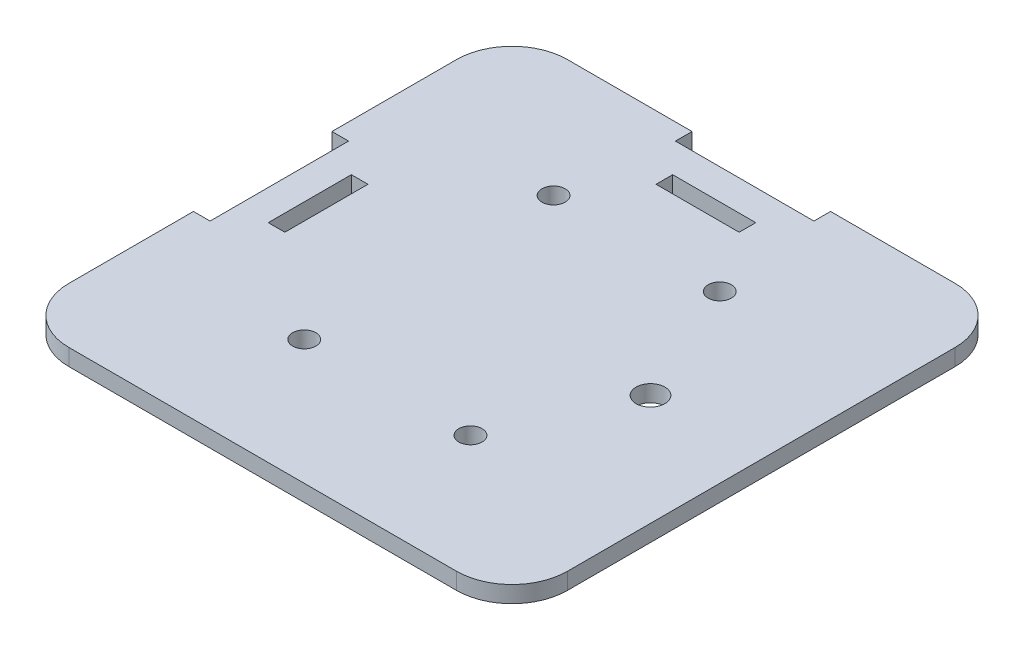
SolidWorks part; units mm, degrees
ref_plane "Front Plane" through (0, 0, 0) normal (0, 0, 1) x (1, 0, 0)
ref_plane "Top Plane" through (0, 0, 0) normal (0, 1, 0) x (1, 0, 0)
ref_plane "Right Plane" through (0, 0, 0) normal (1, 0, 0) x (0, 0, -1)
sketch "Sketch1" plane through (0, 0, 0) normal (0, 1, 0) x (1, 0, 0)
  line L1 (35, -45) -> (-35, -45)
  line L2 (45, -35) -> (45, 35)
  line L3 (35, 45) -> (-35, 45)
  line L4 (-45, -35) -> (-45, 35)
  line L5 (45, -45) -> (-45, 45) construction
  line L6 (45, 45) -> (-45, -45) construction
  line L7 (-45, 12.5) -> (-42, 12.5)
  line L8 (-45, 12.5) -> (-45, -12.5)
  line L9 (-45, -12.5) -> (-42, -12.5)
  line L10 (-42, 12.5) -> (-42, -12.5)
  line L11 (-12.5, 45) -> (12.5, 45)
  line L12 (-12.5, 45) -> (-12.5, 42)
  line L13 (-12.5, 42) -> (12.5, 42)
  line L14 (12.5, 45) -> (12.5, 42)
  arc A0 (-45, -35) -> (-35, -45) centre (-35, -35) ccw
  arc A1 (35, -45) -> (45, -35) centre (35, -35) ccw
  arc A2 (45, 35) -> (35, 45) centre (35, 35) ccw
  arc A3 (-45, 35) -> (-35, 45) centre (-35, 35) cw
  point P0 (0, 0)
  point P22 (-42, 0)
  point P23 (-45, 0)
  point P28 (0, 42)
  point P29 (0, 45)
  dimension "D1" = 10
  dimension "D2" = 3
  dimension "D3" = 25
  dimension "D4" = 0
  dimension "D5" = 3
  dimension "D6" = 25
  dimension "D7" = 0
  dimension "D8" = 90
  dimension "D9" = 90
extrude "Boss-Extrude1" add sketch "Sketch1" along normal blind 3 contours A3 L4 L7 L10 L9 A0 L1 A1 L2 A2 L3 L14 L13 L12
sketch "Sketch2" plane through (0, 3, 0) normal (0, 1, 0) x (1, 0, 0)
  line L0 (0, -1.65) -> (0, 1.65) construction
  line L1 (-1.65, 0) -> (1.65, 0) construction
  circle A0 centre (-15, 22.5) radius 2.1
  circle A1 centre (15, 22.5) radius 2.1
  circle A2 centre (15, -22.5) radius 2.1
  circle A3 centre (-15, -22.5) radius 2.1
  dimension "D1" = 15
  dimension "D2" = 22.5
extrude "Cut-Extrude1" cut sketch "Sketch2" against normal blind 3
sketch "Sketch3" plane through (0, 3, 0) normal (0, 1, 0) x (1, 0, 0)
  line L1 (7.5, 33.5) -> (-7.5, 33.5)
  line L2 (7.5, 33.5) -> (7.5, 36.5)
  line L3 (7.5, 36.5) -> (-7.5, 36.5)
  line L4 (-7.5, 33.5) -> (-7.5, 36.5)
  line L5 (7.5, 33.5) -> (-7.5, 36.5) construction
  line L6 (7.5, 36.5) -> (-7.5, 33.5) construction
  line L7 (-33.5, -7.5) -> (-36.5, -7.5)
  line L8 (-33.5, -7.5) -> (-33.5, 7.5)
  line L9 (-33.5, 7.5) -> (-36.5, 7.5)
  line L10 (-36.5, -7.5) -> (-36.5, 7.5)
  line L11 (-33.5, -7.5) -> (-36.5, 7.5) construction
  line L12 (-33.5, 7.5) -> (-36.5, -7.5) construction
  point P0 (0, 35)
  point P5 (-35, 0)
  dimension "D1" = 15
  dimension "D2" = 3
  dimension "D3" = 35
  dimension "D4" = 0
  dimension "D5" = 3
  dimension "D6" = 15
  dimension "D7" = 0
  dimension "D8" = 35
extrude "Cut-Extrude2" cut sketch "Sketch3" against normal blind 10
sketch "Sketch4" plane through (0, 3, 0) normal (0, 1, 0) x (1, 0, 0)
  circle A0 centre (25, 0) radius 2.6
  dimension "D1" = 25
extrude "Cut-Extrude3" cut sketch "Sketch4" against normal blind 14
